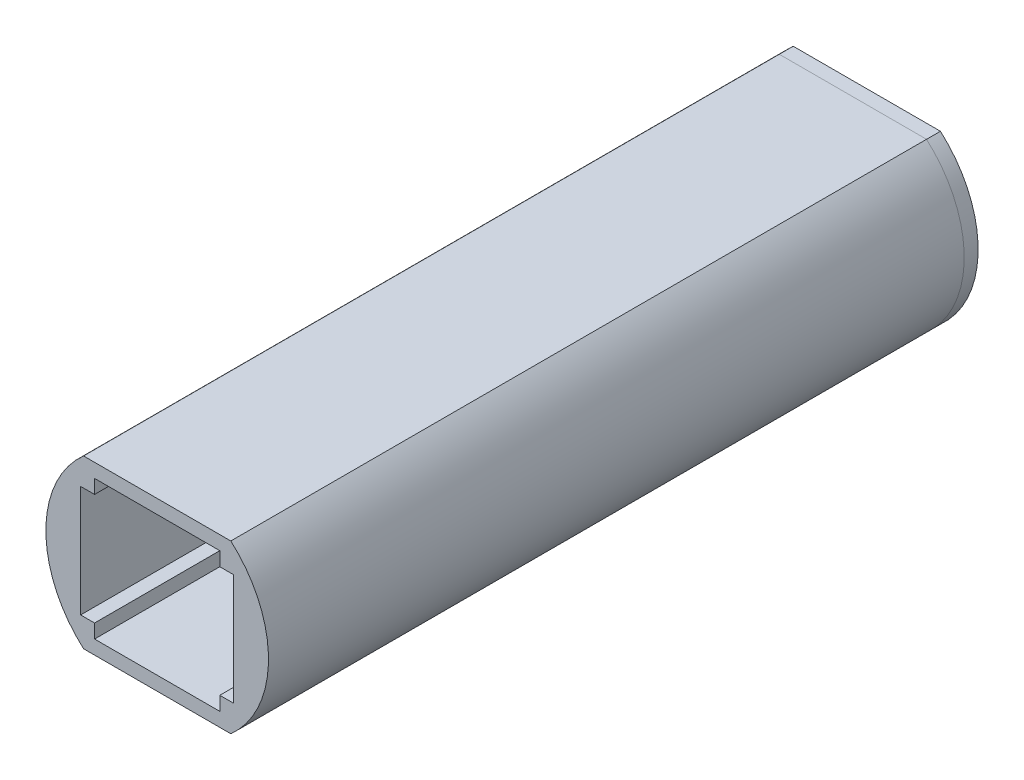
SolidWorks part; units mm, degrees
ref_plane "Front Plane" through (0, 0, 0) normal (0, 0, 1) x (1, 0, 0)
ref_plane "Top Plane" through (0, 0, 0) normal (0, 1, 0) x (1, 0, 0)
ref_plane "Right Plane" through (0, 0, 0) normal (1, 0, 0) x (0, 0, -1)
sketch "Sketch2" plane through (0, 0, 0) normal (0, 0, 1) x (1, 0, 0)
  line L0 (-5.2915, 6) -> (5.2915, 6)
  line L1 (-5.2915, -6) -> (5.2915, -6)
  line L2 (-8, 0) -> (8, 0) construction
  arc A0 (-5.2915, 6) -> (-5.2915, -6) centre (0, 0) ccw
  arc A1 (5.2915, -6) -> (5.2915, 6) centre (0, 0) ccw
  dimension "D1" = 16
  dimension "D2" = 12
extrude "Boss-Extrude1" add sketch "Sketch2" along normal blind 1
sketch "Sketch3" plane through (0, 0, 1) normal (0, 0, 1) x (1, 0, 0)
  line L0 (-5.2915, 6) -> (5.2915, 6)
  line L1 (-5.2915, -6) -> (5.2915, -6)
  line L2 (-8, 0) -> (8, 0) construction
  arc A0 (-5.2915, 6) -> (-5.2915, -6) centre (0, 0) ccw
  arc A1 (5.2915, -6) -> (5.2915, 6) centre (0, 0) ccw
extrude "Boss-Extrude2" add sketch "Sketch3" along normal blind 50 separate body
sketch "Sketch4" plane through (0, 0, 51) normal (0, 0, 1) x (1, 0, 0)
  line L0 (-4.5, 5) -> (-4.5, 4)
  line L1 (4.5, -5) -> (-4.5, -5)
  line L2 (5.5, -4) -> (5.5, 4)
  line L3 (4.5, 5) -> (-4.5, 5)
  line L4 (-5.5, -4) -> (-5.5, 4)
  line L5 (5.5, -5) -> (-5.5, 5) construction
  line L6 (5.5, 5) -> (-5.5, -5) construction
  line L7 (-4.5, 4) -> (-5.5, 4)
  line L8 (0, -0.55) -> (0, 0.55) construction
  line L9 (4.5, 5) -> (4.5, 4)
  line L10 (4.5, 4) -> (5.5, 4)
  line L11 (0.55, 0) -> (-0.55, 0) construction
  line L12 (4.5, -4) -> (5.5, -4)
  line L13 (4.5, -5) -> (4.5, -4)
  line L14 (-4.5, -4) -> (-5.5, -4)
  line L15 (-4.5, -5) -> (-4.5, -4)
  point P0 (0, 0)
  dimension "D1" = 10
  dimension "D2" = 11
  dimension "D3" = 1
extrude "Cut-Extrude1" cut sketch "Sketch4" against normal up to next (50 mm away)
sketch "Sketch5" plane through (0, 0, 0) normal (0, 0, -1) x (-1, 0, 0)
  circle A0 centre (0, 0) radius 4.5
  dimension "D1" = 9
extrude "Cut-Extrude2" cut sketch "Sketch5" against normal up to next (1 mm away)
